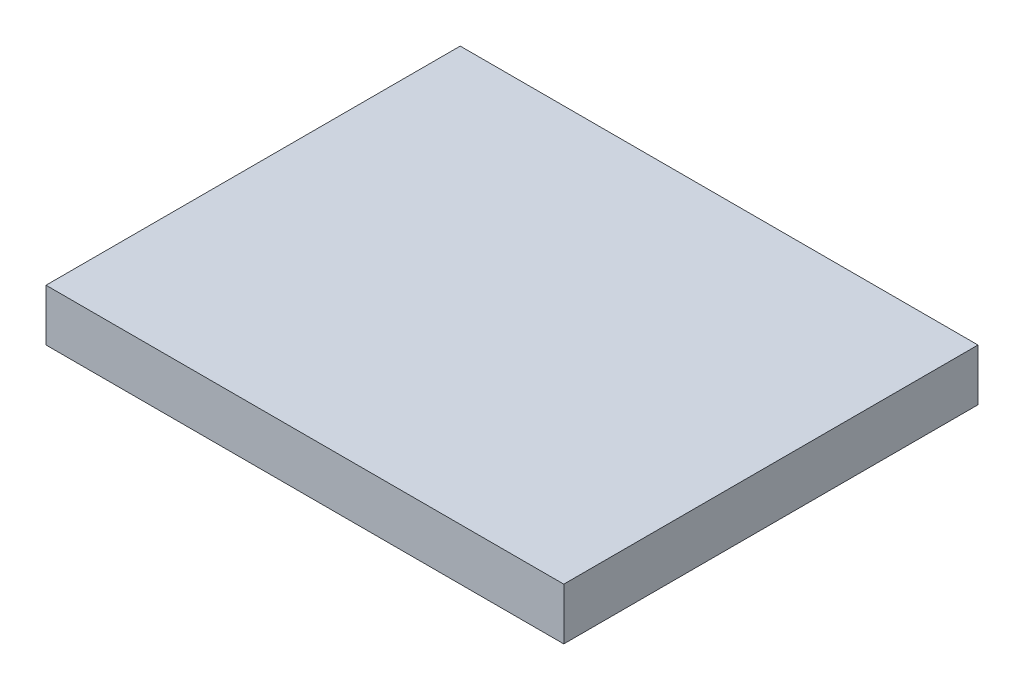
SolidWorks part; units mm, degrees
ref_plane "Front Plane" through (0, 0, 0) normal (0, 0, 1) x (1, 0, 0)
ref_plane "Top Plane" through (0, 0, 0) normal (0, 1, 0) x (1, 0, 0)
ref_plane "Right Plane" through (0, 0, 0) normal (1, 0, 0) x (0, 0, -1)
sketch "Sketch1" plane through (0, 0, 0) normal (0, 1, 0) x (1, 0, 0)
  line L1 (0, 0) -> (-50, 0)
  line L2 (0, 0) -> (0, 40)
  line L3 (0, 40) -> (-50, 40)
  line L4 (-50, 0) -> (-50, 40)
  dimension "D1" = 40
  dimension "D2" = 50
extrude "Boss-Extrude1" add sketch "Sketch1" along normal blind 5
